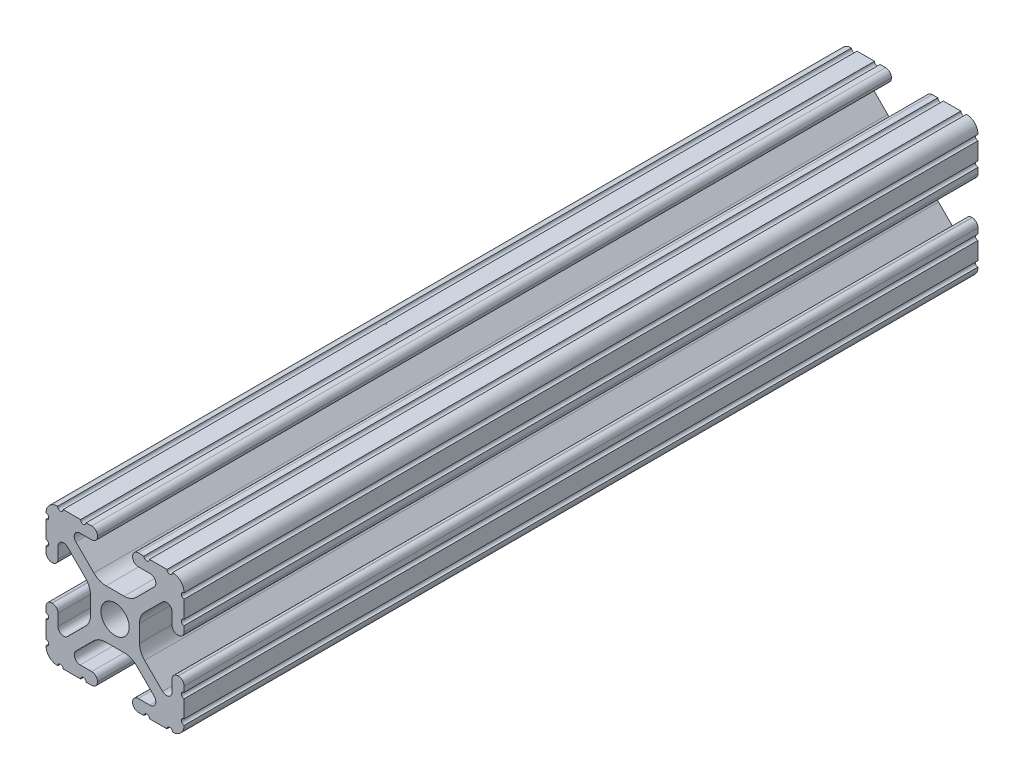
SolidWorks part; units mm, degrees
ref_plane "Front Plane" through (0, 0, 0) normal (0, 0, 1) x (1, 0, 0)
ref_plane "Top Plane" through (0, 0, 0) normal (0, 1, 0) x (1, 0, 0)
ref_plane "Right Plane" through (0, 0, 0) normal (1, 0, 0) x (0, 0, -1)
sketch "Sketch1" plane through (0, 0, 0) normal (0, 0, 1) x (1, 0, 0)
  line L0 (-7.207, 8.7244) -> (-3.8983, 5.4232)
  line L1 (-4.2875, 10.4902) -> (-6.4768, 10.4902)
  line L2 (-3.2385, 11.651) -> (-3.2385, 11.5392)
  line L3 (-5.3171, 12.7) -> (-4.2875, 12.7)
  line L4 (0, 13.4005) -> (0, -14.8534) construction
  line L5 (12.7, 0) -> (-13.9989, 0) construction
  line L6 (-9.5504, 12.7) -> (-6.3331, 12.7)
  line L7 (-12.7, 6.3331) -> (-12.7, 9.5504)
  line L8 (-12.7, 4.2875) -> (-12.7, 5.3171)
  line L9 (-11.5392, 3.2385) -> (-11.651, 3.2385)
  line L10 (-10.4902, 6.4021) -> (-10.4902, 4.2875)
  line L11 (-5.441, 3.8408) -> (-8.7371, 7.1294)
  line L12 (-4.5085, -1.5932) -> (-4.5085, 1.5932)
  line L13 (-1.7093, -4.4958) -> (1.7093, -4.4958)
  line L14 (3.9523, -5.4237) -> (7.1797, -8.6452)
  line L15 (6.4164, -10.4902) -> (4.2875, -10.4902)
  line L16 (3.2385, -11.5392) -> (3.2385, -11.651)
  line L17 (4.2875, -12.7) -> (5.3171, -12.7)
  line L18 (6.3331, -12.7) -> (9.5504, -12.7)
  line L19 (12.7, -9.5504) -> (12.7, -6.3331)
  line L20 (12.7, -5.3171) -> (12.7, -4.2875)
  line L21 (11.651, -3.2385) -> (11.5392, -3.2385)
  line L22 (10.4902, -4.2875) -> (10.4902, -6.4021)
  line L23 (8.7371, -7.1294) -> (5.441, -3.8408)
  line L24 (4.5085, -1.5932) -> (4.5085, 1.5932)
  line L25 (5.441, 3.8408) -> (8.7371, 7.1294)
  line L26 (10.4902, 6.4021) -> (10.4902, 4.2875)
  line L27 (11.5392, 3.2385) -> (11.651, 3.2385)
  line L28 (12.7, 4.2875) -> (12.7, 5.3171)
  line L29 (12.7, 6.3331) -> (12.7, 9.5504)
  line L30 (9.5504, 12.7) -> (6.3331, 12.7)
  line L31 (5.3171, 12.7) -> (4.2875, 12.7)
  line L32 (3.2385, 11.651) -> (3.2385, 11.5392)
  line L33 (4.2875, 10.4902) -> (6.4768, 10.4902)
  line L34 (7.207, 8.7244) -> (3.8983, 5.4232)
  line L35 (1.6558, 4.4958) -> (-1.6558, 4.4958)
  line L36 (-8.7371, -7.1294) -> (-5.441, -3.8408)
  line L37 (-10.4902, -4.2875) -> (-10.4902, -6.4021)
  line L38 (-11.651, -3.2385) -> (-11.5392, -3.2385)
  line L39 (-12.7, -5.3171) -> (-12.7, -4.2875)
  line L40 (-12.7, -9.5504) -> (-12.7, -6.3331)
  line L41 (-6.3331, -12.7) -> (-9.5504, -12.7)
  line L42 (-4.2875, -12.7) -> (-5.3171, -12.7)
  line L43 (-3.2385, -11.5392) -> (-3.2385, -11.651)
  line L44 (-6.4164, -10.4902) -> (-4.2875, -10.4902)
  line L45 (-3.9523, -5.4237) -> (-7.1797, -8.6452)
  arc A0 (-7.207, 8.7244) -> (-6.4768, 10.4902) centre (-6.4768, 9.4563) cw
  arc A1 (-3.2385, 11.5392) -> (-4.2875, 10.4902) centre (-4.2875, 11.5392) cw
  arc A2 (-4.2875, 12.7) -> (-3.2385, 11.651) centre (-4.2875, 11.651) cw
  arc A3 (-5.3171, 12.7) -> (-6.3331, 12.7) centre (-5.8251, 12.7) cw
  arc A4 (-9.5504, 12.7) -> (-10.5664, 12.6998) centre (-10.0584, 12.7) cw
  arc A5 (-12.6998, 10.5664) -> (-10.5664, 12.6998) centre (-10.5918, 10.5918) cw
  arc A6 (-12.6998, 10.5664) -> (-12.7, 9.5504) centre (-12.7, 10.0584) cw
  arc A7 (-12.7, 6.3331) -> (-12.7, 5.3171) centre (-12.7, 5.8251) cw
  arc A8 (-11.651, 3.2385) -> (-12.7, 4.2875) centre (-11.651, 4.2875) cw
  arc A9 (-10.4902, 4.2875) -> (-11.5392, 3.2385) centre (-11.5392, 4.2875) cw
  circle A10 centre (0, 0) radius 2.6035
  arc A11 (-10.4902, 6.4021) -> (-8.7371, 7.1294) centre (-9.4628, 6.4021) cw
  arc A12 (-5.441, 3.8408) -> (-4.5085, 1.5932) centre (-7.6835, 1.5932) cw
  arc A13 (-4.5085, -1.5932) -> (-5.441, -3.8408) centre (-7.6835, -1.5932) cw
  arc A14 (-8.7371, -7.1294) -> (-10.4902, -6.4021) centre (-9.4628, -6.4021) cw
  arc A15 (-1.7093, -4.4958) -> (-3.9523, -5.4237) centre (-1.7093, -7.6708) ccw
  arc A16 (3.9523, -5.4237) -> (1.7093, -4.4958) centre (1.7093, -7.6708) ccw
  arc A17 (6.4164, -10.4902) -> (7.1797, -8.6452) centre (6.4164, -9.4098) ccw
  arc A18 (4.2875, -10.4902) -> (3.2385, -11.5392) centre (4.2875, -11.5392) ccw
  arc A19 (3.2385, -11.651) -> (4.2875, -12.7) centre (4.2875, -11.651) ccw
  arc A20 (6.3331, -12.7) -> (5.3171, -12.7) centre (5.8251, -12.7) ccw
  arc A21 (10.5664, -12.6998) -> (9.5504, -12.7) centre (10.0584, -12.7) ccw
  arc A22 (10.5664, -12.6998) -> (12.6998, -10.5664) centre (10.5918, -10.5918) ccw
  arc A23 (12.7, -9.5504) -> (12.6998, -10.5664) centre (12.7, -10.0584) ccw
  arc A24 (12.7, -5.3171) -> (12.7, -6.3331) centre (12.7, -5.8251) ccw
  arc A25 (12.7, -4.2875) -> (11.651, -3.2385) centre (11.651, -4.2875) ccw
  arc A26 (11.5392, -3.2385) -> (10.4902, -4.2875) centre (11.5392, -4.2875) ccw
  arc A27 (8.7371, -7.1294) -> (10.4902, -6.4021) centre (9.4628, -6.4021) ccw
  arc A28 (4.5085, -1.5932) -> (5.441, -3.8408) centre (7.6835, -1.5932) ccw
  arc A29 (5.441, 3.8408) -> (4.5085, 1.5932) centre (7.6835, 1.5932) ccw
  arc A30 (10.4902, 6.4021) -> (8.7371, 7.1294) centre (9.4628, 6.4021) ccw
  arc A31 (10.4902, 4.2875) -> (11.5392, 3.2385) centre (11.5392, 4.2875) ccw
  arc A32 (11.651, 3.2385) -> (12.7, 4.2875) centre (11.651, 4.2875) ccw
  arc A33 (12.7, 6.3331) -> (12.7, 5.3171) centre (12.7, 5.8251) ccw
  arc A34 (12.6998, 10.5664) -> (12.7, 9.5504) centre (12.7, 10.0584) ccw
  arc A35 (12.6998, 10.5664) -> (10.5664, 12.6998) centre (10.5918, 10.5918) ccw
  arc A36 (9.5504, 12.7) -> (10.5664, 12.6998) centre (10.0584, 12.7) ccw
  arc A37 (5.3171, 12.7) -> (6.3331, 12.7) centre (5.8251, 12.7) ccw
  arc A38 (4.2875, 12.7) -> (3.2385, 11.651) centre (4.2875, 11.651) ccw
  arc A39 (3.2385, 11.5392) -> (4.2875, 10.4902) centre (4.2875, 11.5392) ccw
  arc A40 (7.207, 8.7244) -> (6.4768, 10.4902) centre (6.4768, 9.4563) ccw
  arc A41 (1.6558, 4.4958) -> (3.8983, 5.4232) centre (1.6558, 7.6708) ccw
  arc A42 (-1.6558, 4.4958) -> (-3.8983, 5.4232) centre (-1.6558, 7.6708) cw
  arc A43 (-11.5392, -3.2385) -> (-10.4902, -4.2875) centre (-11.5392, -4.2875) cw
  arc A44 (-12.7, -4.2875) -> (-11.651, -3.2385) centre (-11.651, -4.2875) cw
  arc A45 (-12.7, -5.3171) -> (-12.7, -6.3331) centre (-12.7, -5.8251) cw
  arc A46 (-12.7, -9.5504) -> (-12.6998, -10.5664) centre (-12.7, -10.0584) cw
  arc A47 (-10.5664, -12.6998) -> (-12.6998, -10.5664) centre (-10.5918, -10.5918) cw
  arc A48 (-10.5664, -12.6998) -> (-9.5504, -12.7) centre (-10.0584, -12.7) cw
  arc A49 (-6.3331, -12.7) -> (-5.3171, -12.7) centre (-5.8251, -12.7) cw
  arc A50 (-3.2385, -11.651) -> (-4.2875, -12.7) centre (-4.2875, -11.651) cw
  arc A51 (-4.2875, -10.4902) -> (-3.2385, -11.5392) centre (-4.2875, -11.5392) cw
  arc A52 (-6.4164, -10.4902) -> (-7.1797, -8.6452) centre (-6.4164, -9.4098) cw
  dimension "D1" = 5.207
  dimension "D9" = 14.859
  dimension "D2" = 25.4
  dimension "D3" = 12.7
  dimension "D4" = 6.477
  dimension "D5" = 8.2042
  dimension "D6" = 9.017
  dimension "D8" = 2.2098
  dimension "D10" = 2.2098
extrude "Extrude1" add sketch "Sketch1" against normal blind 146.05
